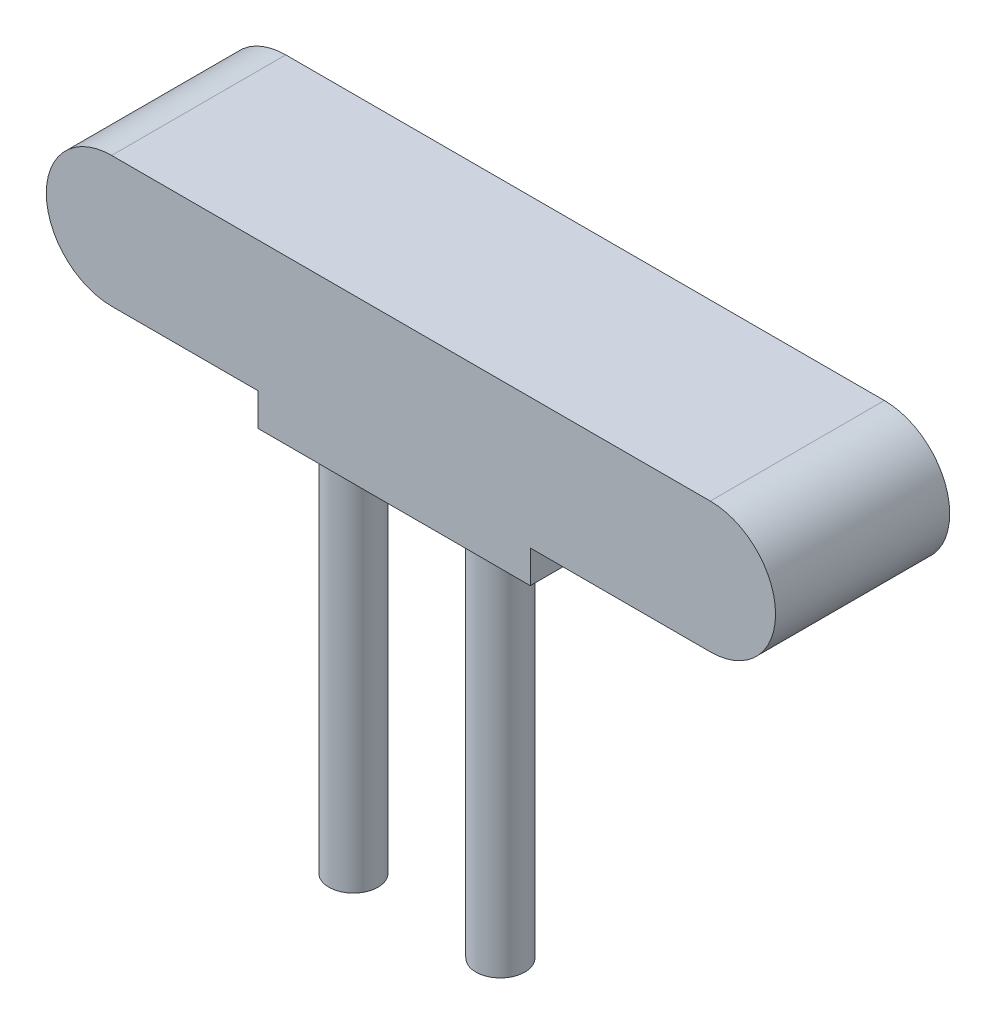
SolidWorks part; units mm, degrees
ref_plane "Front Plane" through (0, 0, 0) normal (0, 0, 1) x (1, 0, 0)
ref_plane "Top Plane" through (0, 0, 0) normal (0, 1, 0) x (1, 0, 0)
ref_plane "Right Plane" through (0, 0, 0) normal (1, 0, 0) x (0, 0, -1)
sketch "Sketch1" plane through (0, 0, 0) normal (0, 1, 0) x (1, 0, 0)
  line L1 (0, 0) -> (63.5, 0)
  line L2 (0, 0) -> (0, 15.24)
  line L3 (0, 15.24) -> (63.5, 15.24)
  line L4 (63.5, 0) -> (63.5, 15.24)
  dimension "D1" = 63.5
  dimension "D2" = 15.24
extrude "Boss-Extrude1" add sketch "Sketch1" along normal blind 7.62
sketch "Sketch2" plane through (0, 0, 0) normal (0, 0, 1) x (1, 0, 0)
  line L5 (0, 7.62) -> (63.5, 7.62) construction
  line L6 (-34.21, 38.1) -> (105.49, 38.1)
  line L8 (-34.21, 7.62) -> (105.49, 7.62)
  arc A0 (105.49, 7.62) -> (105.49, 38.1) centre (105.49, 22.86) ccw
  arc A1 (-34.21, 38.1) -> (-34.21, 7.62) centre (-34.21, 22.86) ccw
  dimension "D2" = 30.48
  dimension "D3" = 0
extrude "Boss-Extrude2" add sketch "Sketch2" against normal blind 40.64
sketch "Sketch3" plane through (0, 0, 0) normal (0, -1, 0) x (1, 0, 0)
  line L1 (0, 0) -> (63.5, 0) construction
  line L2 (0, -15.24) -> (0, 0) construction
  circle A0 centre (14.605, -7.62) radius 5.715
  circle A1 centre (48.895, -7.62) radius 5.715
  point P6 (0, 0)
  point P9 (31.75, 0)
  point P10 (0, -7.62)
  dimension "D1" = 11.43
  dimension "D2" = 11.43
  dimension "D3" = 0
  dimension "D4" = 34.29
  dimension "D5" = 17.145
  dimension "D6" = 0
extrude "Boss-Extrude3" add sketch "Sketch3" along normal blind 86.36
sketch "Sketch4" plane through (0, -86.36, 0) normal (0, -1, 0) x (1, 0, 0)
  circle A0 centre (14.605, -7.62) radius 1.905
  circle A1 centre (48.895, -7.62) radius 1.905
  dimension "D1" = 3.81
  dimension "D2" = 3.81
extrude "Cut-Extrude1" cut sketch "Sketch4" against normal blind 12.7
